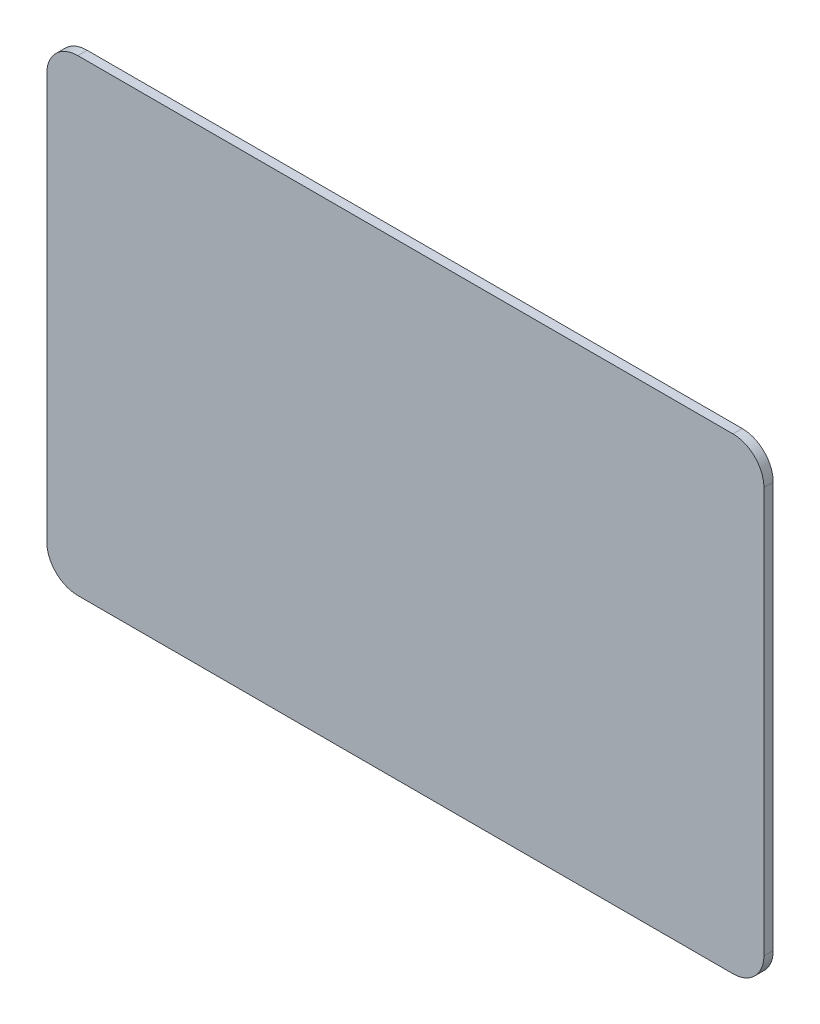
SolidWorks part; units mm, degrees
material "BUTYL"
ref_plane "Plan de face" through (0, 0, 0) normal (0, 0, 1) x (1, 0, 0)
ref_plane "Plan de dessus" through (0, 0, 0) normal (0, 1, 0) x (1, 0, 0)
ref_plane "Plan de droite" through (0, 0, 0) normal (1, 0, 0) x (0, 0, -1)
sketch "Esquisse1" plane through (0, 0, 0) normal (0, 0, 1) x (1, 0, 0)
  line L1 (-52.88, 37.74) -> (52.88, 37.74)
  line L2 (-57.88, 32.74) -> (-57.88, -32.74)
  line L3 (-52.88, -37.74) -> (52.88, -37.74)
  line L4 (57.88, 32.74) -> (57.88, -32.74)
  line L5 (-57.88, 37.74) -> (57.88, -37.74) construction
  line L6 (-57.88, -37.74) -> (57.88, 37.74) construction
  arc A0 (52.88, -37.74) -> (57.88, -32.74) centre (52.88, -32.74) ccw
  arc A1 (-57.88, -32.74) -> (-52.88, -37.74) centre (-52.88, -32.74) ccw
  arc A2 (-52.88, 37.74) -> (-57.88, 32.74) centre (-52.88, 32.74) ccw
  arc A3 (52.88, 37.74) -> (57.88, 32.74) centre (52.88, 32.74) cw
  point P0 (0, 0)
  dimension "D3" = 5
  dimension "D1" = 115.76
  dimension "D2" = 75.48
extrude "Boss.-Extru.1" add sketch "Esquisse1" along normal blind 1.5
